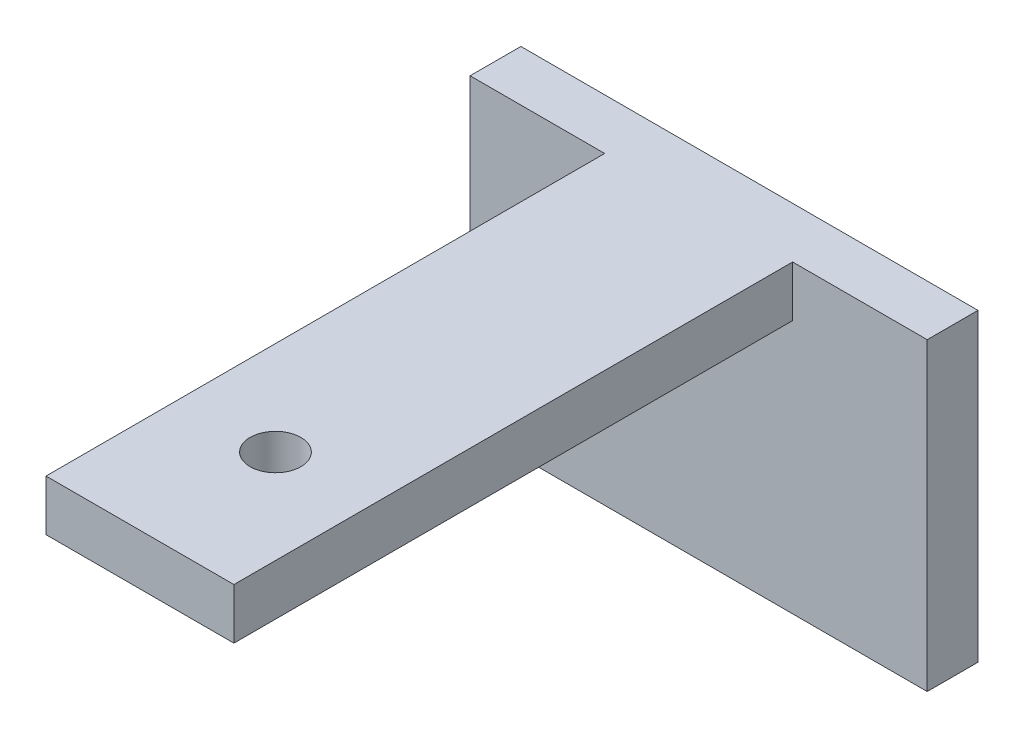
SolidWorks part; units mm, degrees
ref_plane "Front Plane" through (0, 0, 0) normal (0, 0, 1) x (1, 0, 0)
ref_plane "Top Plane" through (0, 0, 0) normal (0, 1, 0) x (1, 0, 0)
ref_plane "Right Plane" through (0, 0, 0) normal (1, 0, 0) x (0, 0, -1)
sketch "Sketch1" plane through (0, 0, 0) normal (0, 0, 1) x (1, 0, 0)
  line L1 (22.5, -15) -> (-22.5, -15)
  line L2 (22.5, -15) -> (22.5, 15)
  line L3 (22.5, 15) -> (-22.5, 15)
  line L4 (-22.5, -15) -> (-22.5, 15)
  line L5 (22.5, -15) -> (-22.5, 15) construction
  line L6 (22.5, 15) -> (-22.5, -15) construction
  point P0 (0, 0)
  dimension "D1" = 45
  dimension "D2" = 30
extrude "Boss-Extrude1" add sketch "Sketch1" along normal blind 5
sketch "Sketch2" plane through (0, 0, 5) normal (0, 0, 1) x (1, 0, 0)
  line L0 (-9.25, 15) -> (9.25, 15)
  line L1 (22.5, 15) -> (-22.5, 15) construction
  line L2 (9.25, 15) -> (9.25, 10)
  line L3 (9.25, 10) -> (-9.25, 10)
  line L4 (-9.25, 10) -> (-9.25, 15)
  line L5 (22.5, -15) -> (22.5, 15) construction
  point P5 (0, 15)
  dimension "D1" = 18.5
  dimension "D2" = 5
  dimension "D3" = 22.5
extrude "Boss-Extrude2" add sketch "Sketch2" along normal blind 55
sketch "Sketch3" plane through (0, 15, 0) normal (0, 1, 0) x (1, 0, 0)
  line L0 (0, -60) -> (0, 0) construction
  line L1 (9.25, -60) -> (-9.25, -60) construction
  circle A0 centre (0, -46.66) radius 2.5
  dimension "D2" = 5
  dimension "D1" = 13.34
extrude "Cut-Extrude1" cut sketch "Sketch3" against normal blind 10
